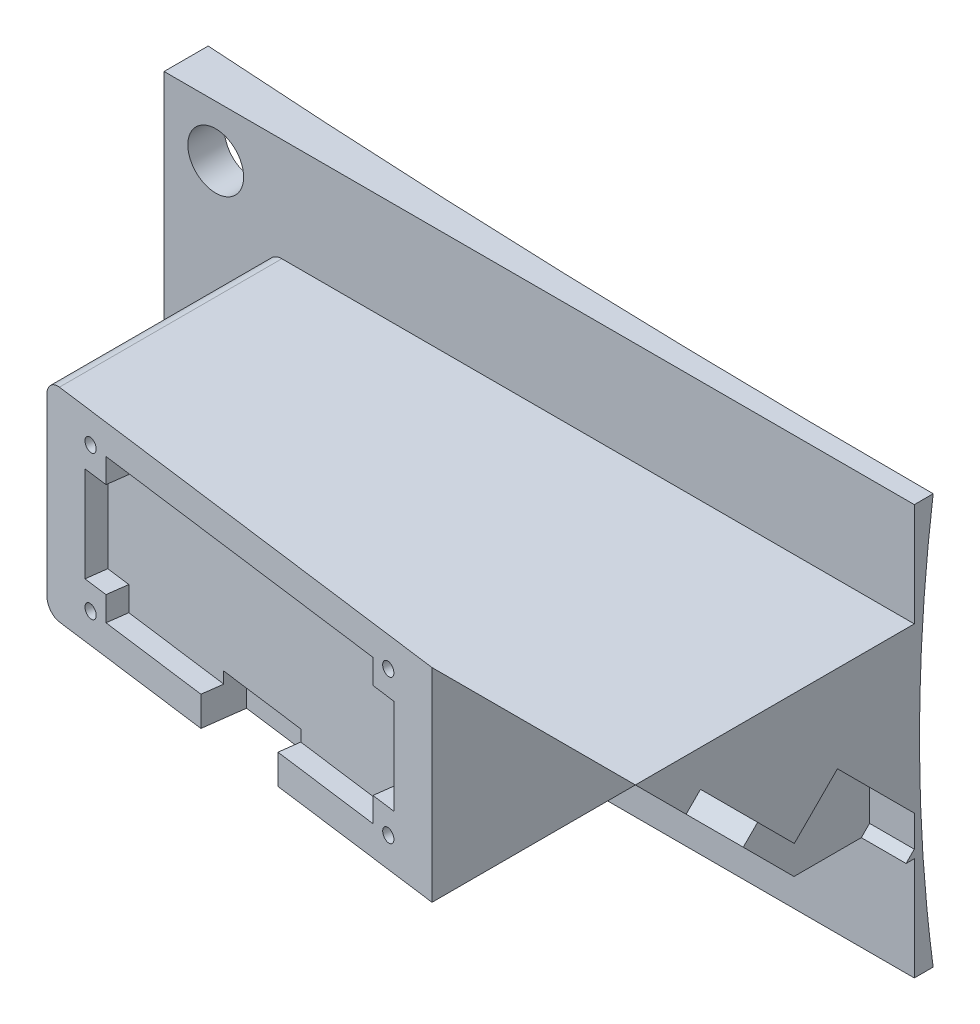
SolidWorks part; units mm, degrees
material "Nylon 101"
ref_plane "Front Plane" through (0, 0, 0) normal (0, 0, 1) x (1, 0, 0)
ref_plane "Top Plane" through (0, 0, 0) normal (0, 1, 0) x (1, 0, 0)
ref_plane "Right Plane" through (0, 0, 0) normal (1, 0, 0) x (0, 0, -1)
sketch "Sketch6" plane through (0, 0, 0) normal (0, 1, 0) x (1, 0, 0)
  line L6 (-79.5295, 0) -> (79.5295, 0)
  line L7 (-79.5295, 0) -> (-79.5295, -56.3211)
  line L8 (-79.5295, -56.3211) -> (-25, -63.5)
  line L9 (-25, -63.5) -> (25, -63.5)
  line L10 (25, -63.5) -> (79.5295, -56.3211)
  line L11 (79.5295, -56.3211) -> (79.5295, 0)
  line L12 (0, -63.5) -> (0, 0) construction
  point P4 (0, 0)
  point P10 (0, -63.5)
  dimension "D1" = 172.5
  dimension "D2" = 55
  dimension "D3" = 63.5
  dimension "D4" = 50
extrude "Boss-Extrude4" add sketch "Sketch6" along normal blind 25
sketch "Sketch7" plane through (0, 0, 0) normal (1, 0, 0) x (0, 0, -1)
  line L0 (-63.5, 25) -> (-38.5, 0)
  line L1 (-63.5, 0) -> (-56.3211, 0) construction
  line L2 (-63.5, 25) -> (-63.5, 0) construction
  line L3 (-63.5, 25) -> (-63.5, 0)
  line L4 (-63.5, 0) -> (-38.5, 0)
  dimension "D1" = 45
extrude "Cut-Extrude2" cut sketch "Sketch7" against normal mid plane 50
hole_wizard "Tap Drill for #4-40 Tap1" positions "Sketch9" profile "Sketch10" hole size "#4-40" standard "ANSI Inch"
sketch "Sketch9" plane through (0, -19.25, 19.25) normal (0, -0.7071, 0.7071) x (-1, 0, 0)
  line L0 (21.255, -53.7563) -> (21.255, -36.0463) construction
  line L2 (25, -27.2236) -> (25, -62.579) construction
  line L3 (21.255, -53.7563) -> (-21.255, -53.7563) construction
  line L5 (25, -62.579) -> (-25, -62.579) construction
  point P0 (-21.255, -53.7563)
  point P2 (21.255, -53.7563)
  point P4 (21.255, -36.0463)
  point P6 (-21.255, -36.0463)
  point P18 (21.255, -44.9013)
  point P21 (25, -44.9013)
  point P29 (0, -53.7563)
  point P32 (0, -62.579)
  dimension "D1" = 42.51
  dimension "D2" = 17.71
sketch "Sketch10" plane through (21.255, 18.7614, 57.2614) normal (1, 0, 0) x (0, -0.7071, -0.7071)
  line L0 (0, 0) -> (0, 8.3547)
  line L1 (0, 8.3547) -> (0.8, 7.874)
  line L2 (0.8, 7.874) -> (0.8, 0)
  line L5 (0.8, 0) -> (0, 0)
  line L10 (0, 8.3547) -> (-0.8, 7.874) construction
  line L11 (0, -6.35) -> (0, 107.95) construction
  dimension "Hole Dia." = 1.6
  dimension "Hole Depth" = 7.874
  dimension "Drill Angle" = 118
hole_wizard "Tap Drill for #4-40 Tap3" positions "Sketch14" profile "Sketch15" hole size "#4-40" standard "ANSI Inch"
sketch "Sketch14" plane through (-8.6434, 0, 65.6534) normal (-0.1305, 0, 0.9914) x (0.9914, 0, 0.1305)
  line L2 (-22.7427, 21.355) -> (-65.2527, 21.355) construction
  line L3 (-65.2527, 21.355) -> (-65.2527, 3.645) construction
  line L5 (-71.4977, 25) -> (-16.4977, 25) construction
  line L6 (-71.4977, 25) -> (-71.4977, 0) construction
  point P0 (-65.2527, 21.355)
  point P12 (-22.7427, 21.355)
  point P13 (-22.7427, 3.645)
  point P14 (-65.2527, 3.645)
  point P26 (-43.9977, 21.355)
  point P29 (-43.9977, 25)
  point P30 (-65.2527, 12.5)
  point P33 (-71.4977, 12.5)
  dimension "D3" = 42.51
  dimension "D4" = 17.71
  dimension "D1" = 2
  dimension "D2" = 2
sketch "Sketch15" plane through (-73.3379, 21.355, 57.1362) normal (0, 1, 0) x (0.9914, 0, 0.1305)
  line L0 (0, 0) -> (0, 8.3547)
  line L1 (0, 8.3547) -> (0.8, 7.874)
  line L2 (0.8, 7.874) -> (0.8, 0)
  line L5 (0.8, 0) -> (0, 0)
  line L10 (0, 8.3547) -> (-0.8, 7.874) construction
  line L11 (0, -6.35) -> (0, 107.95) construction
  dimension "Hole Dia." = 1.6
  dimension "Hole Depth" = 7.874
  dimension "Drill Angle" = 118
hole_wizard "Tap Drill for #4-40 Tap4" positions "Sketch18" profile "Sketch19" hole size "#4-40" standard "ANSI Inch"
sketch "Sketch18" plane through (8.6434, 0, 65.6534) normal (0.1305, 0, 0.9914) x (0.9914, 0, -0.1305)
  line L2 (22.7427, 3.645) -> (22.7427, 21.355) construction
  line L3 (22.7427, 21.355) -> (65.2527, 21.355) construction
  line L6 (16.4977, 25) -> (71.4977, 25) construction
  line L7 (16.4977, 25) -> (16.4977, 0) construction
  point P0 (22.7427, 21.355)
  point P9 (65.2527, 21.355)
  point P10 (65.2527, 3.645)
  point P11 (22.7427, 3.645)
  point P22 (43.9977, 21.355)
  point P25 (43.9977, 25)
  point P26 (22.7427, 12.5)
  point P29 (16.4977, 12.5)
  dimension "D3" = 42.51
  dimension "D4" = 17.71
  dimension "D1" = 2
  dimension "D2" = 2
sketch "Sketch19" plane through (31.1916, 21.355, 62.6849) normal (0, 1, 0) x (0.9914, 0, -0.1305)
  line L0 (0, 0) -> (0, 8.3547)
  line L1 (0, 8.3547) -> (0.8, 7.874)
  line L2 (0.8, 7.874) -> (0.8, 0)
  line L5 (0.8, 0) -> (0, 0)
  line L10 (0, 8.3547) -> (-0.8, 7.874) construction
  line L11 (0, -6.35) -> (0, 107.95) construction
  dimension "Hole Dia." = 1.6
  dimension "Hole Depth" = 7.874
  dimension "Drill Angle" = 118
fillet "Fillet1" radius 1.778 4 edges at (79.5295, 25, 28.1605) (79.5295, 0, 28.1605) (-79.5295, 0, 28.1605) (-79.5295, 25, 28.1605)
sketch "Sketch20" plane through (-8.6434, 0, 65.6534) normal (-0.1305, 0, 0.9914) x (0.9914, 0, 0.1305)
  line L0 (-63.0527, 21.355) -> (-63.0527, 18.355)
  line L1 (-63.0527, 18.355) -> (-66.0527, 18.355)
  line L2 (-66.0527, 18.355) -> (-66.0527, 6.645)
  line L3 (-66.0527, 6.645) -> (-63.0527, 6.645)
  line L4 (-63.0527, 6.645) -> (-63.0527, 3.645)
  line L5 (-63.0527, 3.645) -> (-24.9427, 3.645)
  line L6 (-24.9427, 3.645) -> (-24.9427, 6.645)
  line L7 (-24.9427, 6.645) -> (-21.9427, 6.645)
  line L8 (-21.9427, 6.645) -> (-21.9427, 18.355)
  line L9 (-21.9427, 18.355) -> (-24.9427, 18.355)
  line L10 (-24.9427, 18.355) -> (-24.9427, 21.355)
  line L11 (-24.9427, 21.355) -> (-63.0527, 21.355)
  circle A2 centre (-65.2527, 21.355) radius 0.8 construction
  circle A3 centre (-65.2527, 21.355) radius 0.8 construction
  circle A4 centre (-22.7427, 21.355) radius 0.8 construction
  point P11 (-66.0527, 21.355)
  point P14 (-21.9427, 21.355)
  dimension "D1" = 3
  dimension "D2" = 3
sketch "Sketch21" plane through (8.6434, 0, 65.6534) normal (0.1305, 0, 0.9914) x (0.9914, 0, -0.1305)
  line L0 (24.9427, 21.355) -> (24.9427, 18.355)
  line L1 (24.9427, 18.355) -> (21.9427, 18.355)
  line L2 (21.9427, 18.355) -> (21.9427, 6.645)
  line L3 (21.9427, 6.645) -> (24.9427, 6.645)
  line L4 (24.9427, 6.645) -> (24.9427, 3.645)
  line L5 (24.9427, 3.645) -> (63.0527, 3.645)
  line L6 (63.0527, 3.645) -> (63.0527, 6.645)
  line L7 (63.0527, 6.645) -> (66.0527, 6.645)
  line L8 (66.0527, 6.645) -> (66.0527, 18.355)
  line L9 (66.0527, 18.355) -> (63.0527, 18.355)
  line L10 (63.0527, 18.355) -> (63.0527, 21.355)
  line L11 (63.0527, 21.355) -> (24.9427, 21.355)
  circle A0 centre (22.7427, 21.355) radius 0.8 construction
  circle A1 centre (22.7427, 21.355) radius 0.8 construction
  circle A2 centre (65.2527, 21.355) radius 0.8 construction
  circle A3 centre (65.2527, 21.355) radius 0.8 construction
  point P11 (21.9427, 21.355)
  point P14 (66.0527, 21.355)
  dimension "D1" = 3
  dimension "D2" = 3
sketch "Sketch22" plane through (0, -19.25, 19.25) normal (0, -0.7071, 0.7071) x (1, 0, 0)
  line L0 (-19.055, 53.7563) -> (-19.055, 50.7563)
  line L1 (-19.055, 50.7563) -> (-22.055, 50.7563)
  line L2 (-22.055, 50.7563) -> (-22.055, 39.0463)
  line L3 (-22.055, 39.0463) -> (-19.055, 39.0463)
  line L4 (-19.055, 39.0463) -> (-19.055, 36.0463)
  line L5 (-19.055, 36.0463) -> (19.055, 36.0463)
  line L6 (19.055, 36.0463) -> (19.055, 39.0463)
  line L7 (19.055, 39.0463) -> (22.055, 39.0463)
  line L8 (22.055, 39.0463) -> (22.055, 50.7563)
  line L9 (22.055, 50.7563) -> (19.055, 50.7563)
  line L10 (19.055, 50.7563) -> (19.055, 53.7563)
  line L11 (19.055, 53.7563) -> (-19.055, 53.7563)
  circle A0 centre (-21.255, 53.7563) radius 0.8 construction
  circle A1 centre (-21.255, 53.7563) radius 0.8 construction
  circle A2 centre (21.255, 53.7563) radius 0.8 construction
  circle A3 centre (21.255, 53.7563) radius 0.8 construction
  point P18 (22.055, 53.7563)
  point P25 (-22.055, 53.7563)
  dimension "D1" = 3
  dimension "D2" = 3
extrude "Cut-Extrude3" cut sketch "Sketch22" against normal blind 2.5
extrude "Cut-Extrude4" cut sketch "Sketch21" against normal blind 2.5 contours L5 L6 L7 L8 L9 L10 L11 L0 L1 L2 L3 L4
extrude "Cut-Extrude5" cut sketch "Sketch20" against normal blind 2.5 contours L5 L6 L7 L8 L9 L10 L11 L0 L1 L2 L3 L4
sketch "Sketch23" plane through (8.6434, 0, 65.6534) normal (0.1305, 0, 0.9914) x (0.9914, 0, -0.1305)
  line L1 (38.4977, 5.045) -> (49.4977, 5.045)
  line L2 (38.4977, 5.045) -> (38.4977, 0)
  line L3 (38.4977, 0) -> (49.4977, 0)
  line L4 (49.4977, 5.045) -> (49.4977, 0)
  line L5 (24.9427, 3.645) -> (63.0527, 3.645) construction
  line L6 (24.9427, 3.645) -> (63.0527, 3.645) construction
  line L7 (16.4977, 0) -> (69.7044, 0) construction
  point P0 (43.9977, 5.045)
  point P12 (43.9977, 3.645)
  dimension "D1" = 11
  dimension "D2" = 1.4
extrude "Cut-Extrude6" cut sketch "Sketch23" against normal blind 5
sketch "Sketch24" plane through (-8.6434, 0, 65.6534) normal (-0.1305, 0, 0.9914) x (0.9914, 0, 0.1305)
  line L0 (-49.4977, 5.045) -> (-38.4977, 5.045)
  line L1 (-49.4977, 5.045) -> (-49.4977, 0)
  line L2 (-49.4977, 0) -> (-38.4977, 0)
  line L3 (-38.4977, 5.045) -> (-38.4977, 0)
  line L4 (-63.0527, 3.645) -> (-24.9427, 3.645) construction
  line L5 (-69.7044, 0) -> (-16.4977, 0) construction
  point P0 (-43.9977, 5.045)
  point P7 (-43.9977, 3.645)
  dimension "D1" = 11
  dimension "D2" = 1.4
extrude "Cut-Extrude7" cut sketch "Sketch24" against normal blind 5
sketch "Sketch25" plane through (0, -19.25, 19.25) normal (0, -0.7071, 0.7071) x (1, 0, 0)
  line L0 (-5.5, 37.4463) -> (5.5, 37.4463)
  line L1 (-5.5, 37.4463) -> (-5.5, 21.3712)
  line L2 (-5.5, 21.3712) -> (5.5, 21.3712)
  line L3 (5.5, 37.4463) -> (5.5, 21.3712)
  line L4 (-19.055, 36.0463) -> (19.055, 36.0463) construction
  point P0 (0, 37.4463)
  point P7 (0, 36.0463)
  dimension "D1" = 11
  dimension "D2" = 1.4
extrude "Cut-Extrude8" cut sketch "Sketch25" against normal blind 10 contours L3 L2 L1 L0
sketch "Sketch26" plane through (0, 0, 0) normal (0, 0, -1) x (-1, 0, 0)
  line L0 (-77.7515, 25) -> (77.7515, 25) construction
  line L1 (-92.2295, -12.7) -> (92.2295, -12.7)
  line L2 (-92.2295, -12.7) -> (-92.2295, 37.7)
  line L3 (-92.2295, 37.7) -> (92.2295, 37.7)
  line L4 (92.2295, -12.7) -> (92.2295, 37.7)
  line L5 (-92.2295, -12.7) -> (92.2295, 37.7) construction
  line L6 (-92.2295, 37.7) -> (92.2295, -12.7) construction
  line L7 (-79.5295, 23.222) -> (-79.5295, 1.778) construction
  point P0 (0, 12.5)
  point P9 (0, 37.7)
  point P11 (-92.2295, 12.5)
  point P12 (-79.5295, 12.5)
  dimension "D1" = 12.7
  dimension "D2" = 12.7
extrude "Boss-Extrude6" add sketch "Sketch26" against normal blind 29.21
sketch "Sketch11" plane through (0, 0, 0) normal (1, 0, 0) x (0, 0, -1)
  line L0 (-28.575, 12.5) -> (1344.295, 12.5) construction
  line L1 (0, 25) -> (0, 0) construction
  line L2 (1344.295, -496.77) -> (1344.295, 521.77)
  ellipse E0 centre (1344.295, 12.5) end of major axis (-28.575, 12.5) minor radius 509.27 (1344.295, 521.77) -> (1344.295, -496.77) ccw
  point P7 (1344.295, 12.5)
  point P15 (0, 12.5)
  dimension "D1" = 1372.87
  dimension "D2" = 1018.54
  dimension "D3" = 28.575
revolve "Cut-Revolve4" cut sketch "Sketch11" angle 360 about L2
sketch "Sketch27" plane through (0, 0, 29.21) normal (0, 0, 1) x (1, 0, 0)
  line L0 (92.2295, 37.7) -> (92.2295, -12.7) construction
  line L1 (92.2295, -12.7) -> (-92.2295, -12.7) construction
  line L2 (-92.2295, 37.7) -> (92.2295, 37.7) construction
  line L3 (-92.2295, -12.7) -> (-92.2295, 37.7) construction
  circle A0 centre (85.8795, -6.35) radius 3.429
  circle A1 centre (-85.8795, -6.35) radius 3.429
  circle A2 centre (-85.8795, 31.35) radius 3.429
  circle A3 centre (85.8795, 31.35) radius 3.429
  dimension "D1" = 6.858
  dimension "D2" = 6.35
  dimension "D6" = 6.35
  dimension "D7" = 6.35
  dimension "D3" = 6.35
  dimension "D4" = 2
  dimension "D5" = 2
extrude "Cut-Extrude9" cut sketch "Sketch27" against normal through all
sketch "Sketch28" plane through (0, 0, 0) normal (1, 0, 0) x (0, 0, -1)
  line L1 (-195.3253, -113.1307) -> (18.0963, -113.1307)
  line L2 (-195.3253, -113.1307) -> (-195.3253, 52.1263)
  line L3 (-195.3253, 52.1263) -> (18.0963, 52.1263)
  line L4 (18.0963, -113.1307) -> (18.0963, 52.1263)
  line L5 (-195.3253, -113.1307) -> (18.0963, 52.1263) construction
  line L6 (-195.3253, 52.1263) -> (18.0963, -113.1307) construction
  point P0 (-88.6145, -30.5022)
extrude "Cut-Extrude10" cut sketch "Sketch28" along normal through all contours L4 L3 L2 L1
